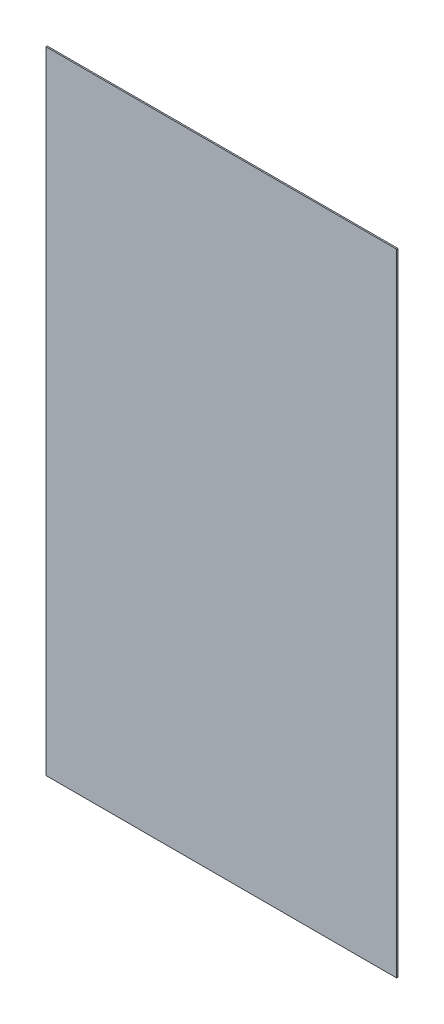
SolidWorks part; units mm, degrees
ref_plane "Alzado" through (0, 0, 0) normal (0, 0, 1) x (1, 0, 0)
ref_plane "Planta" through (0, 0, 0) normal (0, 1, 0) x (1, 0, 0)
ref_plane "Vista lateral" through (0, 0, 0) normal (1, 0, 0) x (0, 0, -1)
sketch "Croquis1" plane through (0, 0, 0) normal (0, 0, 1) x (1, 0, 0)
  line L1 (-250, 450) -> (250, 450)
  line L2 (-250, 450) -> (-250, -450)
  line L3 (-250, -450) -> (250, -450)
  line L4 (250, 450) -> (250, -450)
  line L5 (-250, 450) -> (250, -450) construction
  line L6 (-250, -450) -> (250, 450) construction
  point P0 (0, 0)
  dimension "D1" = 500
  dimension "D2" = 900
extrude "Saliente-Extruir1" add sketch "Croquis1" along normal blind 1.9
